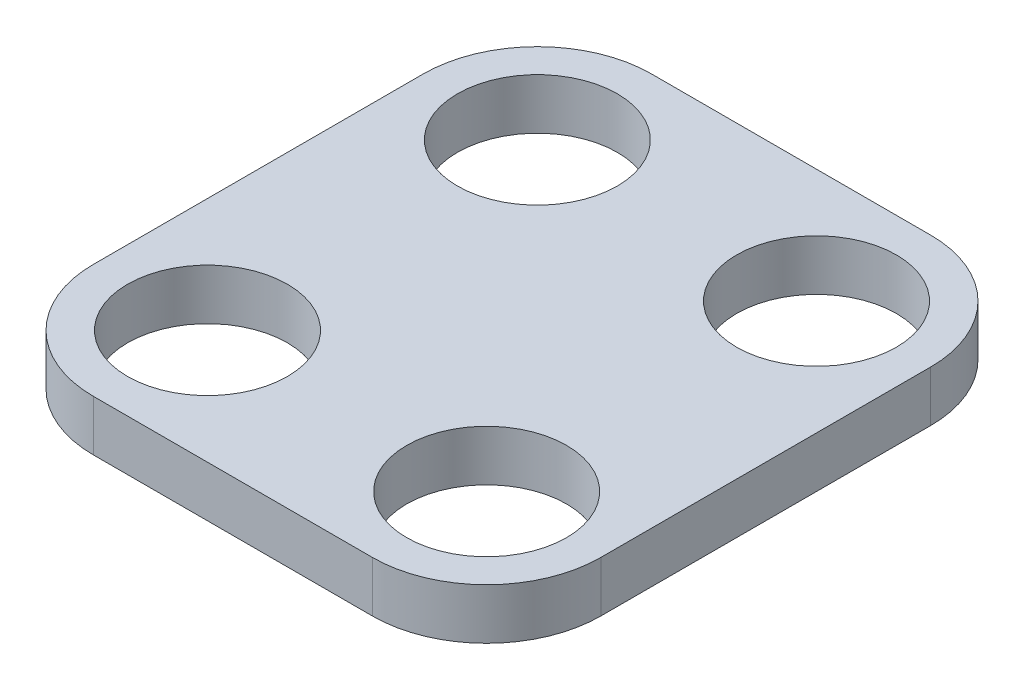
SolidWorks part; units mm, degrees
material "Copper"
ref_plane "Front Plane" through (0, 0, 0) normal (0, 0, 1) x (1, 0, 0)
ref_plane "Top Plane" through (0, 0, 0) normal (0, 1, 0) x (1, 0, 0)
ref_plane "Right Plane" through (0, 0, 0) normal (1, 0, 0) x (0, 0, -1)
sketch "Sketch2" plane through (0, 0, 0) normal (0, 1, 0) x (1, 0, 0)
  line L0 (5.6071, -29.4973) -> (-1.9695, -29.4973) construction
  line L1 (0.5536, -40.4973) -> (11.5536, -40.4973)
  line L2 (6.5, -29.4973) -> (14.0766, -29.4973) construction
  line L3 (-3.9464, -22.9973) -> (-3.9464, -35.9973)
  line L5 (0.5536, -18.4973) -> (11.5536, -18.4973)
  line L9 (6.0536, -22.4973) -> (6.0536, -36.4973) construction
  line L12 (16.0536, -22.9973) -> (16.0536, -35.9973)
  circle A0 centre (11.5536, -35.9973) radius 3.15
  arc A1 (11.5536, -18.4973) -> (16.0536, -22.9973) centre (11.5536, -22.9973) cw
  circle A2 centre (11.5536, -22.9973) radius 3.15
  arc A3 (11.5536, -40.4973) -> (16.0536, -35.9973) centre (11.5536, -35.9973) ccw
  arc A4 (0.5536, -40.4973) -> (-3.9464, -35.9973) centre (0.5536, -35.9973) cw
  circle A5 centre (0.5536, -22.9973) radius 3.15
  arc A6 (0.5536, -18.4973) -> (-3.9464, -22.9973) centre (0.5536, -22.9973) ccw
  circle A7 centre (0.5536, -35.9973) radius 3.15
  point P1 (4.9434, -43.007)
  point P13 (8, -83.1034)
  point P20 (7.1638, -43.007)
  dimension "D1" = 6.3
  dimension "D2" = 4.5
  dimension "D3" = 13
  dimension "D4" = 11
extrude "Boss-Extrude1" add sketch "Sketch2" against normal blind 2
